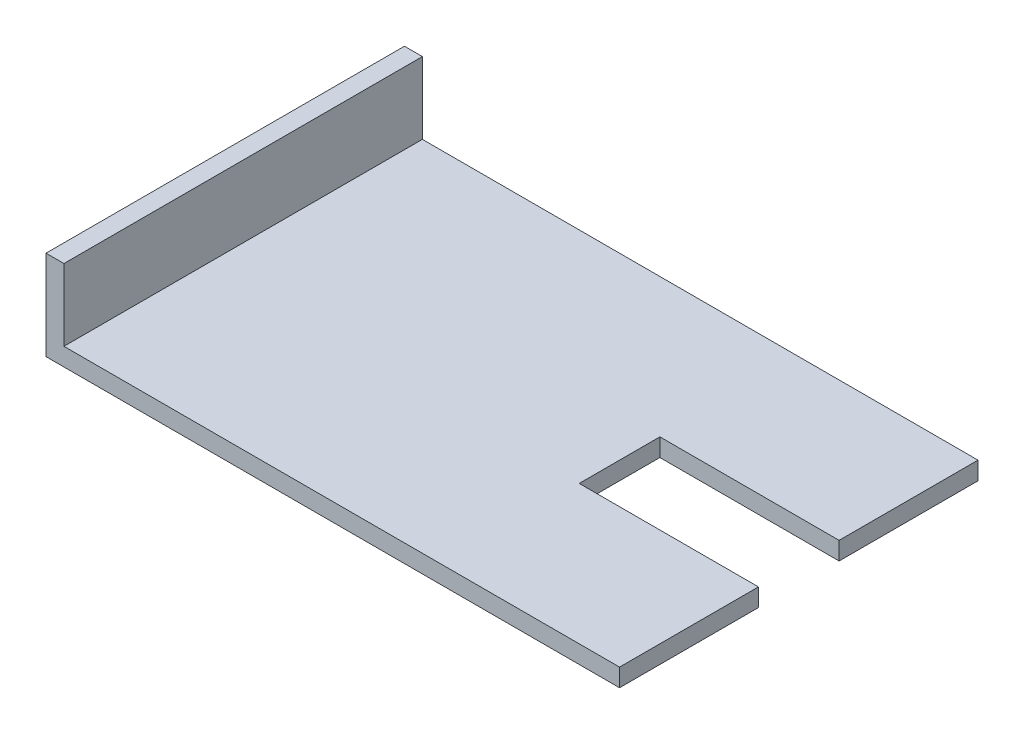
SolidWorks part; units mm, degrees
ref_plane "Plan de face" through (0, 0, 0) normal (0, 0, 1) x (1, 0, 0)
ref_plane "Plan de dessus" through (0, 0, 0) normal (0, 1, 0) x (1, 0, 0)
ref_plane "Plan de droite" through (0, 0, 0) normal (1, 0, 0) x (0, 0, -1)
sketch "Esquisse1" plane through (0, 0, 0) normal (0, 0, 1) x (1, 0, 0)
  line L1 (0, 0) -> (320, 0)
  line L2 (0, 0) -> (0, 10)
  line L3 (0, 10) -> (320, 10)
  line L4 (320, 0) -> (320, 10)
  line L5 (0, 0) -> (10, 0)
  line L6 (0, 0) -> (0, 50)
  line L7 (0, 50) -> (10, 50)
  line L8 (10, 0) -> (10, 50)
  dimension "D1" = 10
  dimension "D2" = 50
  dimension "D3" = 320
extrude "Boss.-Extru.1" add sketch "Esquisse1" along normal blind 200 contours L8 L1 L4 L3 | L3 L8 L7 L6 | L1 L8 L3 L2
sketch "Esquisse4" plane through (0, 10, 0) normal (0, 1, 0) x (1, 0, 0)
  line L0 (320, -200) -> (320, 0) construction
  line L1 (320, -77.5) -> (220, -77.5)
  line L2 (320, -77.5) -> (320, -122.5)
  line L3 (320, -122.5) -> (220, -122.5)
  line L4 (220, -77.5) -> (220, -122.5)
  line L5 (10, -100) -> (320, -100) construction
  line L6 (10, -200) -> (10, 0) construction
  point P10 (220, -100)
  dimension "D1" = 45
  dimension "D2" = 100
extrude "Enlèv. mat.-Extru.1" cut sketch "Esquisse4" against normal blind 10
